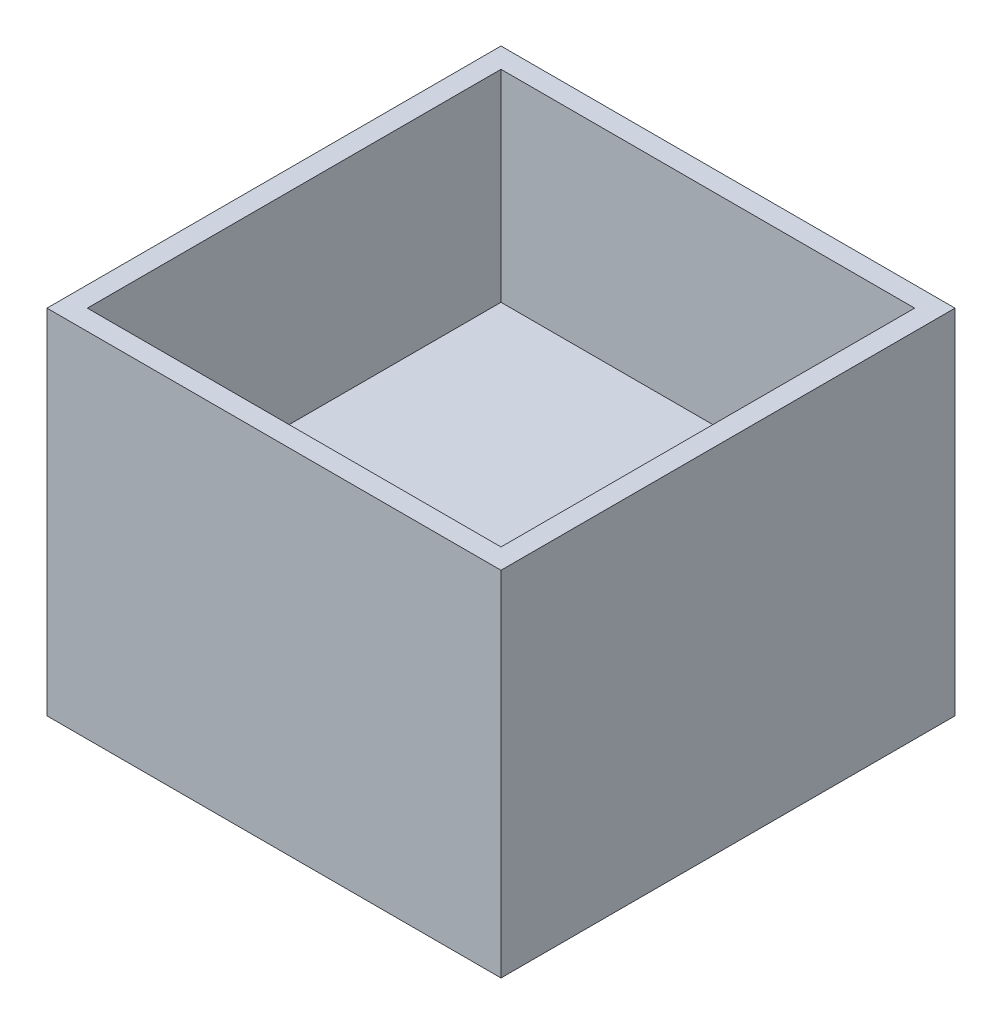
SolidWorks part; units mm, degrees
ref_plane "Front Plane" through (0, 0, 0) normal (0, 0, 1) x (1, 0, 0)
ref_plane "Top Plane" through (0, 0, 0) normal (0, 1, 0) x (1, 0, 0)
ref_plane "Right Plane" through (0, 0, 0) normal (1, 0, 0) x (0, 0, -1)
sketch "Sketch1" plane through (0, 0, 0) normal (0, 1, 0) x (1, 0, 0)
  line L1 (0, 0) -> (45, 0)
  line L2 (0, 0) -> (0, 45)
  line L3 (0, 45) -> (45, 45)
  line L4 (45, 0) -> (45, 45)
  dimension "D1" = 45
  dimension "D2" = 45
extrude "Boss-Extrude1" add sketch "Sketch1" along normal blind 35
sketch "Sketch3" plane through (0, 35, 0) normal (0, 1, 0) x (1, 0, 0)
  line L0 (2, 43) -> (43, 43)
  line L1 (43, 43) -> (43, 2)
  line L2 (43, 2) -> (2, 2)
  line L3 (2, 2) -> (2, 43)
  line L4 (45, 45) -> (0, 45) construction
  line L5 (45, 0) -> (45, 45) construction
  line L6 (0, 0) -> (45, 0) construction
  line L7 (0, 45) -> (0, 0) construction
  dimension "D1" = 2
  dimension "D2" = 2
  dimension "D3" = 2
  dimension "D4" = 2
extrude "Cut-Extrude2" cut sketch "Sketch3" against normal blind 20
